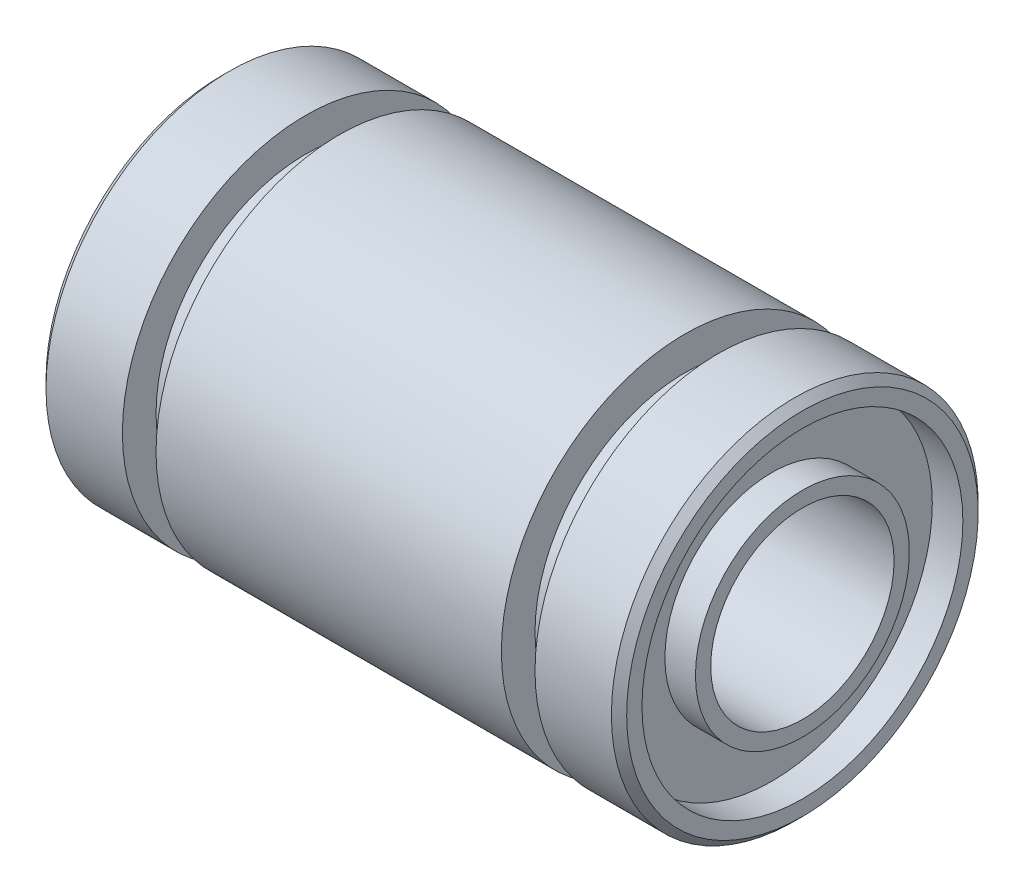
SolidWorks part; units mm, degrees
material "1060 Alloy"
ref_plane "Front Plane" through (0, 0, 0) normal (0, 0, 1) x (1, 0, 0)
ref_plane "Top Plane" through (0, 0, 0) normal (0, 1, 0) x (1, 0, 0)
ref_plane "Right Plane" through (0, 0, 0) normal (1, 0, 0) x (0, 0, -1)
sketch "Sketch1" plane through (0, 0, 0) normal (0, 0, 1) x (1, 0, 0)
  line L0 (-45.6895, 0) -> (45.6895, 0) construction
  line L1 (-9.25, 6) -> (-6.75, 6)
  line L2 (-6.75, 6) -> (-6.75, 4.9)
  line L3 (-6.75, 4.9) -> (-5.65, 4.9)
  line L4 (-5.65, 4.9) -> (-5.65, 6)
  line L5 (-5.65, 6) -> (5.65, 6)
  line L6 (0, 45.6895) -> (0, -45.6895) construction
  line L7 (-9.25, 6) -> (-9.5, 5.75)
  line L8 (-9.5, 5.75) -> (-9.5, 5.25)
  line L9 (-9.5, 5.25) -> (-8.5, 5.25)
  line L10 (-8.5, 5.25) -> (-8.5, 3.5)
  line L11 (-8.5, 3.5) -> (-9.5, 3.5)
  line L12 (-9.5, 3.5) -> (-9.5, 3)
  line L13 (-9.5, 3) -> (9.5, 3)
  line L14 (9.5, 3.5) -> (9.5, 3)
  line L15 (8.5, 3.5) -> (9.5, 3.5)
  line L16 (8.5, 5.25) -> (8.5, 3.5)
  line L17 (9.5, 5.25) -> (8.5, 5.25)
  line L18 (9.5, 5.75) -> (9.5, 5.25)
  line L19 (9.25, 6) -> (9.5, 5.75)
  line L20 (5.65, 4.9) -> (5.65, 6)
  line L21 (6.75, 4.9) -> (5.65, 4.9)
  line L22 (6.75, 6) -> (6.75, 4.9)
  line L23 (9.25, 6) -> (6.75, 6)
  point P19 (0, 3)
  point P26 (0, 6)
  dimension "D1" = 45
  dimension "D2" = 1.1
  dimension "D3" = 0.5
  dimension "L" = 19
  dimension "B" = 13.5
  dimension "W" = 1.1
  dimension "D" = 6
  dimension "D_1" = 5.75
  dimension "D4" = 0.5
  dimension "dr" = 3
  dimension "D5" = 1
revolve "Revolve1" add sketch "Sketch1" angle 360 about L0
equation "\"D\"=12"
equation "\"D1\"=11.5"
equation "\"dr\"=6"
equation "\"L\"=19"
equation "\"B\"=13.5"
equation "\"W\"=1.1"
equation "\"L@Sketch1\"= \"L\""
equation "\"B@Sketch1\"= \"B\""
equation "\"W@Sketch1\"= \"W\""
equation "\"dr@Sketch1\"= \"dr\" * 0.5"
equation "\"D@Sketch1\" = \"D\" * 0.5"
equation "\"D_1@Sketch1\" = \"D1\" * 0.5"
